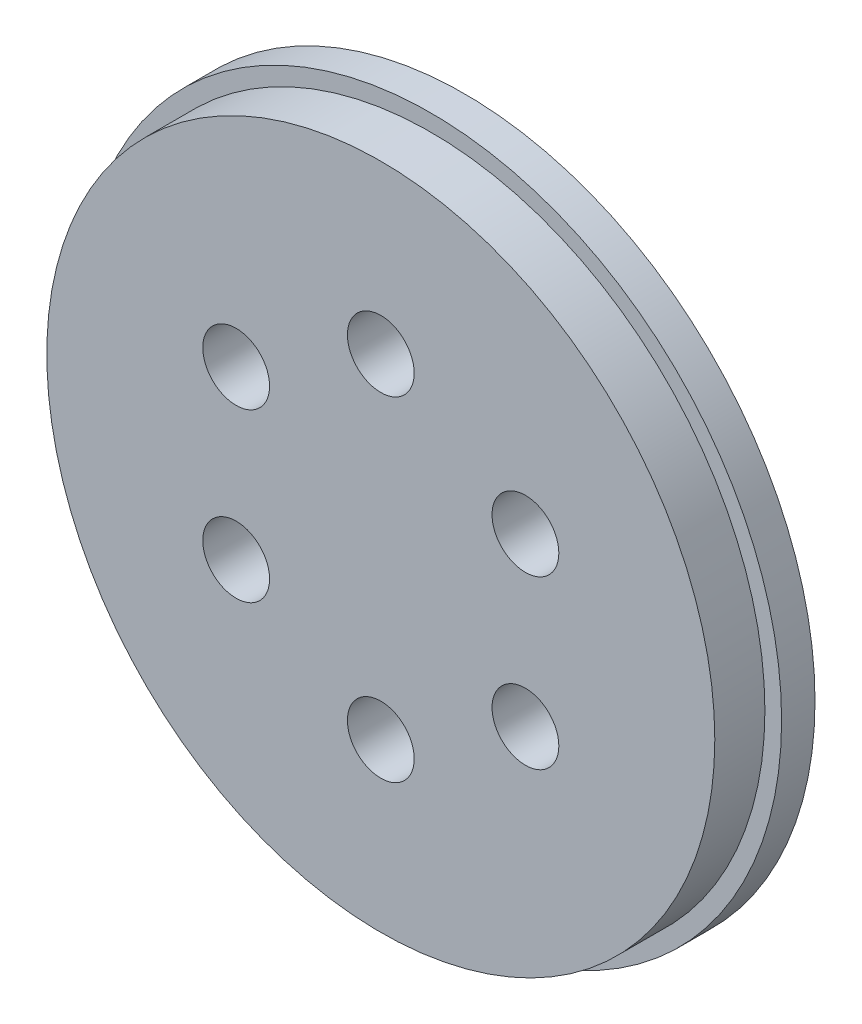
SolidWorks part; units mm, degrees
ref_plane "前视基准面" through (0, 0, 0) normal (0, 0, 1) x (1, 0, 0)
ref_plane "上视基准面" through (0, 0, 0) normal (0, 1, 0) x (1, 0, 0)
ref_plane "右视基准面" through (0, 0, 0) normal (1, 0, 0) x (0, 0, -1)
other "质心 (COM)"
sketch "草图1" plane through (0, 0, 0) normal (0, 0, 1) x (1, 0, 0)
  circle A0 centre (0, 0) radius 21
  dimension "D1" = 42
extrude "凸台-拉伸1" add sketch "草图1" along normal blind 2
sketch "草图2" plane through (0, 0, 2) normal (0, 0, 1) x (1, 0, 0)
  circle A0 centre (0, 0) radius 20
  dimension "D1" = 40
extrude "凸台-拉伸2" add sketch "草图2" along normal blind 3
sketch "草图3" plane through (0, 0, 5) normal (0, 0, 1) x (1, 0, 0)
  circle A0 centre (0, 10) radius 2
  circle A1 centre (8.6603, 5) radius 2
  circle A2 centre (8.6603, -5) radius 2
  circle A3 centre (0, -10) radius 2
  circle A4 centre (-8.6603, -5) radius 2
  circle A5 centre (-8.6603, 5) radius 2
  point P15 (0, 0)
  dimension "D1" = 4
  dimension "D2" = 10
  dimension "D3" = 6
extrude "切除-拉伸1" cut sketch "草图3" against normal through all
